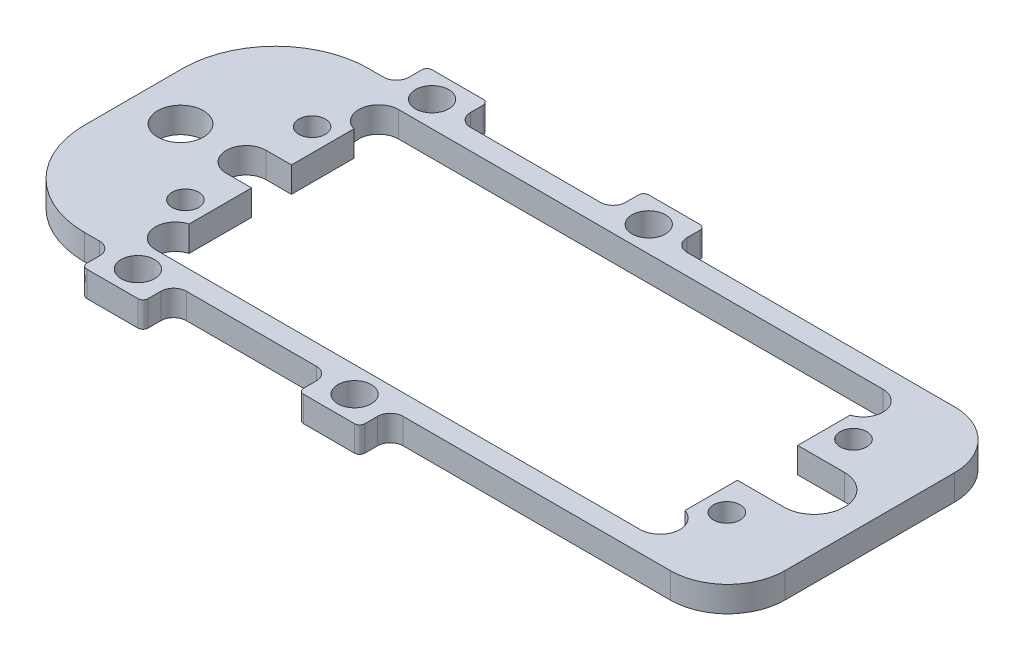
SolidWorks part; units mm, degrees
ref_plane "Alzado" through (0, 0, 0) normal (0, 0, 1) x (1, 0, 0)
ref_plane "Planta" through (0, 0, 0) normal (0, 1, 0) x (1, 0, 0)
ref_plane "Vista lateral" through (0, 0, 0) normal (1, 0, 0) x (0, 0, -1)
ref_plane "Plano1" through (0, 0, 0) normal (0, -1, 0) x (1, 0, 0)
sketch "Croquis1" plane through (0, 0, 0) normal (0, -1, 0) x (1, 0, 0)
  line L0 (-6.0223, -19.2405) -> (-6.0223, -20.828)
  line L1 (-5.3873, -21.463) -> (0.9627, -21.463)
  line L2 (1.5977, -20.828) -> (1.5977, -19.2405)
  line L3 (3.1852, -17.653) -> (36.4312, -17.653)
  line L4 (43.5348, -10.5494) -> (43.5348, 10.5494)
  line L5 (36.4312, 17.653) -> (3.1852, 17.653)
  line L6 (1.5977, 19.2405) -> (1.5977, 20.828)
  line L7 (0.9627, 21.463) -> (-5.3873, 21.463)
  line L8 (-6.0223, 20.828) -> (-6.0223, 19.2405)
  line L9 (-7.6098, 17.653) -> (-23.7556, 17.653)
  line L10 (-25.3431, 19.2405) -> (-25.3431, 20.828)
  line L11 (-25.9781, 21.463) -> (-32.3281, 21.463)
  line L12 (-32.9631, 20.828) -> (-32.9631, 19.2405)
  line L13 (-34.5506, 17.653) -> (-36.4312, 17.653)
  line L14 (-47.971, 6.1133) -> (-47.971, -6.1133)
  line L15 (-36.4312, -17.653) -> (-34.5506, -17.653)
  line L16 (-32.9631, -19.2405) -> (-32.9631, -20.828)
  line L17 (-32.3281, -21.463) -> (-25.9781, -21.463)
  line L18 (-25.3431, -20.828) -> (-25.3431, -19.2405)
  line L19 (-23.7556, -17.653) -> (-7.6098, -17.653)
  line L20 (-33.9725, 2.4765) -> (-30.8275, 2.4765)
  line L21 (-30.8275, 2.4765) -> (-30.8275, 10.2462)
  line L22 (-30.1432, 15.1028) -> (30.1022, 15.1028)
  line L23 (30.845, 10.2638) -> (30.845, 2.4765)
  line L24 (30.845, 2.4765) -> (33.9725, 2.4765)
  line L25 (33.9725, -2.4765) -> (30.845, -2.4765)
  line L26 (30.845, -2.4765) -> (30.845, -10.2638)
  line L27 (30.0923, -15.0997) -> (-30.1324, -15.0997)
  line L28 (-30.8275, -10.2462) -> (-30.8275, -2.4765)
  line L29 (-30.8275, -2.4765) -> (-33.9725, -2.4765)
  circle A0 centre (33.655, -7.874) radius 1.3525
  circle A1 centre (-33.655, 7.874) radius 1.3525
  circle A2 centre (-33.655, -7.874) radius 1.3525
  circle A3 centre (-2.2123, 18.288) radius 1.778
  circle A4 centre (-29.1531, -18.288) radius 1.778
  circle A5 centre (-2.2123, -18.288) radius 1.778
  arc A6 (-6.0223, -20.828) -> (-5.3873, -21.463) centre (-5.3873, -20.828) ccw
  arc A7 (0.9627, -21.463) -> (1.5977, -20.828) centre (0.9627, -20.828) ccw
  arc A8 (1.5977, -19.2405) -> (3.1852, -17.653) centre (3.1852, -19.2405) cw
  arc A9 (36.4312, -17.653) -> (43.5348, -10.5494) centre (36.4312, -10.5494) ccw
  arc A10 (43.5348, 10.5494) -> (36.4312, 17.653) centre (36.4312, 10.5494) ccw
  arc A11 (3.1852, 17.653) -> (1.5977, 19.2405) centre (3.1852, 19.2405) cw
  arc A12 (1.5977, 20.828) -> (0.9627, 21.463) centre (0.9627, 20.828) ccw
  arc A13 (-5.3873, 21.463) -> (-6.0223, 20.828) centre (-5.3873, 20.828) ccw
  arc A14 (-6.0223, 19.2405) -> (-7.6098, 17.653) centre (-7.6098, 19.2405) cw
  arc A15 (-23.7556, 17.653) -> (-25.3431, 19.2405) centre (-23.7556, 19.2405) cw
  arc A16 (-25.3431, 20.828) -> (-25.9781, 21.463) centre (-25.9781, 20.828) ccw
  arc A17 (-32.3281, 21.463) -> (-32.9631, 20.828) centre (-32.3281, 20.828) ccw
  arc A18 (-32.9631, 19.2405) -> (-34.5506, 17.653) centre (-34.5506, 19.2405) cw
  arc A19 (-36.4312, 17.653) -> (-47.971, 6.1133) centre (-36.4312, 6.1133) ccw
  arc A20 (-47.971, -6.1133) -> (-36.4312, -17.653) centre (-36.4312, -6.1133) ccw
  arc A21 (-34.5506, -17.653) -> (-32.9631, -19.2405) centre (-34.5506, -19.2405) cw
  arc A22 (-32.9631, -20.828) -> (-32.3281, -21.463) centre (-32.3281, -20.828) ccw
  arc A23 (-25.9781, -21.463) -> (-25.3431, -20.828) centre (-25.9781, -20.828) ccw
  arc A24 (-25.3431, -19.2405) -> (-23.7556, -17.653) centre (-23.7556, -19.2405) cw
  arc A25 (-7.6098, -17.653) -> (-6.0223, -19.2405) centre (-7.6098, -19.2405) cw
  circle A26 centre (-29.1531, 18.288) radius 1.778
  circle A27 centre (33.655, 7.874) radius 1.3525
  arc A28 (-30.8275, 10.2462) -> (-30.1432, 15.1028) centre (-30.1432, 12.6263) cw
  arc A29 (30.1022, 15.1028) -> (30.845, 10.2638) centre (30.1022, 12.6263) cw
  arc A30 (33.9725, 2.4765) -> (33.9725, -2.4765) centre (33.9725, 0) cw
  arc A31 (30.845, -10.2638) -> (30.0923, -15.0997) centre (30.0923, -12.6232) cw
  arc A32 (-30.1324, -15.0997) -> (-30.8275, -10.2462) centre (-30.1324, -12.6232) cw
  arc A33 (-33.9725, -2.4765) -> (-33.9725, 2.4765) centre (-33.9725, 0) cw
extrude "Saliente-Extruir1" add sketch "Croquis1" against normal blind 3.175
sketch "Croquis5" plane through (0, 3.175, 0) normal (0, 1, 0) x (1, 0, 0)
  line L0 (-39.5889, 0) -> (-42.1389, 0) construction
  line L1 (-36.449, 0) -> (-39.5889, 0) construction
  line L2 (-44.6889, 0) -> (-47.971, 0) construction
  line L3 (-47.971, -6.1133) -> (-47.971, 6.1133) construction
  arc A0 (-33.9725, 2.4765) -> (-33.9725, -2.4765) centre (-33.9725, 0) ccw construction
  circle A1 centre (-42.1389, 0) radius 2.55
extrude "Cortar-Extruir1" cut sketch "Croquis5" against normal through all
sketch "Croquis8" plane through (0, 3.175, 0) normal (0, 1, 0) x (1, 0, 0)
  line L0 (43.5348, 0) -> (38.5379, 0) construction
  line L1 (43.5348, 10.5494) -> (43.5348, -10.5494) construction
sketch "Croquis9" plane through (0, 3.175, 0) normal (0, 1, 0) x (1, 0, 0)
  line L0 (30.845, 2.4765) -> (33.9725, 2.4765) construction
  line L1 (30.845, 2.4765) -> (33.9725, 2.4765) construction
  line L2 (33.9725, -2.4765) -> (30.845, -2.4765) construction
  line L3 (33.9725, -2.4765) -> (30.845, -2.4765) construction
  line L4 (30.845, 2.4765) -> (30.845, -2.4765) construction
  line L5 (30.845, 0) -> (30.845, 3.75) construction
  line L6 (30.845, 10.2638) -> (30.845, 2.4765) construction
  line L7 (30.845, 0) -> (30.845, -3.75) construction
  line L8 (30.845, -2.4765) -> (30.845, -10.2638) construction
  line L9 (30.845, -3.75) -> (36.645, -3.75)
  line L10 (30.845, 3.75) -> (36.645, 3.75)
  arc A0 (33.9725, -2.4765) -> (33.9725, 2.4765) centre (33.9725, 0) ccw construction
  arc A1 (33.9725, -2.4765) -> (33.9725, 2.4765) centre (33.9725, 0) ccw construction
  arc A2 (36.645, 3.75) -> (36.645, -3.75) centre (36.645, 0) cw
  dimension "D1" = 3.75
  dimension "D2" = 3.75
  dimension "D3" = 5.8
extrude "Cortar-Extruir2" cut sketch "Croquis9" against normal through all and the other way through all
sketch "Croquis10" plane through (0, 3.175, 0) normal (0, 1, 0) x (1, 0, 0)
  circle A0 centre (-29.1531, 18.288) radius 2.078
  circle A1 centre (-33.655, 7.874) radius 1.6526
  circle A2 centre (-42.1389, 0) radius 2.85
  circle A3 centre (-33.655, -7.874) radius 1.6526
  circle A4 centre (-29.1531, -18.288) radius 2.078
  circle A5 centre (-2.2123, -18.288) radius 2.078
  circle A6 centre (-2.2123, 18.288) radius 2.078
  circle A7 centre (33.655, 7.874) radius 1.6526
  circle A8 centre (33.655, -7.874) radius 1.6526
  dimension "D1" = 3.3051
  dimension "D2" = 3.3051
  dimension "D3" = 4.156
  dimension "D4" = 4.156
  dimension "D5" = 4.156
  dimension "D6" = 4.156
  dimension "D7" = 3.3051
  dimension "D8" = 3.3051
  dimension "D9" = 5.7
extrude "Cortar-Extruir3" cut sketch "Croquis10" against normal through all
